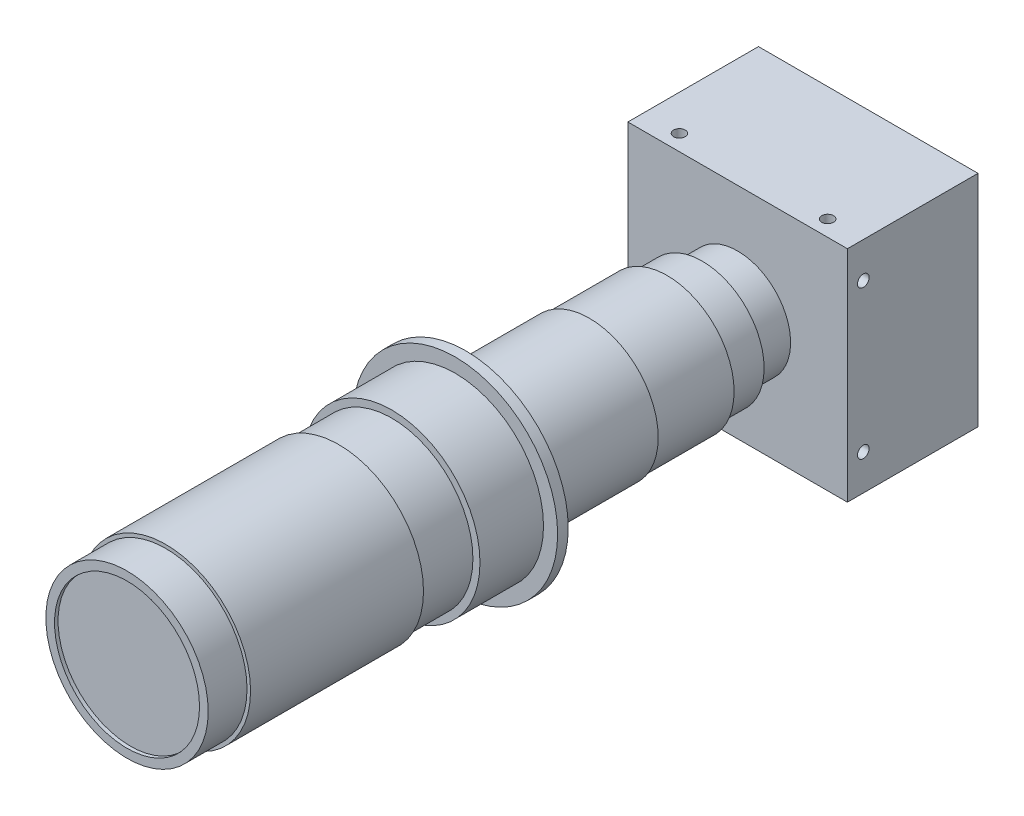
SolidWorks part; units mm, degrees
material "铝合金 (2)"
ref_plane "前基準面" through (0, 0, 0) normal (0, 0, 1) x (1, 0, 0)
ref_plane "上基準面" through (0, 0, 0) normal (0, 1, 0) x (1, 0, 0)
ref_plane "右基準面" through (0, 0, 0) normal (1, 0, 0) x (0, 0, -1)
sketch "草图1" plane through (0, 0, 0) normal (0, 0, 1) x (1, 0, 0)
  line L1 (0, 0) -> (62.2, 0)
  line L2 (0, 0) -> (0, 62.2)
  line L3 (0, 62.2) -> (62.2, 62.2)
  line L4 (62.2, 0) -> (62.2, 62.2)
  dimension "D1" = 62.2
extrude "凸台-拉伸1" add sketch "草图1" along normal blind 37
sketch "草图2" plane through (0, 0, 37) normal (0, 0, 1) x (1, 0, 0)
  line L0 (31.1, 62.2) -> (31.1, 0) construction
  line L1 (62.2, 62.2) -> (0, 62.2) construction
  line L2 (0, 0) -> (62.2, 0) construction
  circle A0 centre (31.1, 31.1) radius 15
  dimension "D1" = 30
extrude "凸台-拉伸2" add sketch "草图2" along normal blind 10
sketch "草图3" plane through (0, 0, 47) normal (0, 0, 1) x (1, 0, 0)
  circle A0 centre (31.1, 31.1) radius 17.5
  dimension "D1" = 35
extrude "凸台-拉伸3" add sketch "草图3" along normal blind 10
sketch "草图4" plane through (0, 0, 57) normal (0, 0, 1) x (1, 0, 0)
  circle A0 centre (31.1, 31.1) radius 19
  dimension "D1" = 38
extrude "凸台-拉伸4" add sketch "草图4" along normal blind 22
sketch "草图5" plane through (0, 0, 79) normal (0, 0, 1) x (1, 0, 0)
  circle A0 centre (31.1, 31.1) radius 19.5
  dimension "D1" = 39
extrude "凸台-拉伸5" add sketch "草图5" along normal blind 35
sketch "草图6" plane through (0, 0, 114) normal (0, 0, 1) x (1, 0, 0)
  circle A0 centre (31.1, 31.1) radius 29
  dimension "D1" = 58
extrude "凸台-拉伸6" add sketch "草图6" along normal blind 3
sketch "草图7" plane through (0, 0, 117) normal (0, 0, 1) x (1, 0, 0)
  circle A0 centre (31.1, 31.1) radius 25
  dimension "D1" = 50
extrude "凸台-拉伸7" add sketch "草图7" along normal blind 18
sketch "草图8" plane through (0, 0, 135) normal (0, 0, 1) x (1, 0, 0)
  circle A0 centre (31.1, 31.1) radius 23
  dimension "D1" = 46
sketch "草图9" plane through (0, 0, 0) normal (0, 0, -1) x (-1, 0, 0)
  circle A0 centre (-16.5763, 47.3033) radius 3.4696
  circle A1 centre (-16.5763, 47.3033) radius 4.9876
extrude "凸台-拉伸8" add sketch "草图9" along normal blind 7
sketch "草图10" plane through (0, 0, 0) normal (0, 0, -1) x (-1, 0, 0)
  line L1 (-24.6285, 18.2507) -> (-16.4054, 18.2507)
  line L2 (-24.6285, 18.2507) -> (-24.6285, 13.1265)
  line L3 (-24.6285, 13.1265) -> (-16.4054, 13.1265)
  line L4 (-16.4054, 18.2507) -> (-16.4054, 13.1265)
extrude "切除-拉伸2" cut sketch "草图10" against normal blind 3
hole_wizard "M4 螺纹孔1" positions "草图12" profile "草图11" tap size "M4" standard "ISO"
sketch "草图12" plane through (0, 62.2, 0) normal (0, 1, 0) x (-1, 0, 0)
  line L0 (-31.1, 37) -> (-31.1, 20.8859) construction
  line L1 (-62.2, 37) -> (0, 37) construction
  point P0 (-10.1, 32.5)
  point P1 (-52.1, 32.5)
  dimension "D1" = 42
  dimension "D2" = 4.5
sketch "草图11" plane through (10.1, 62.2, 32.5) normal (1, 0, 0) x (0, 0, 1)
  line L0 (0, 0) -> (0, 11.0914)
  line L1 (0, 11.0914) -> (1.65, 10.1)
  line L2 (1.65, 10.1) -> (1.65, 0)
  line L5 (1.65, 0) -> (0, 0)
  line L10 (0, 11.0914) -> (-1.65, 10.1) construction
  line L11 (0, -6.35) -> (0, 107.95) construction
  dimension "螺纹孔钻头直径" = 3.3
  dimension "螺纹孔钻头深度" = 10.1
  dimension "导头角度" = 118
cosmetic thread "孔螺蚊线1" parameters "D1"=8, "D2"=4
cosmetic thread "孔螺蚊线2" parameters "D1"=8, "D2"=4
hole_wizard "M4 螺纹孔2" positions "草图14" profile "草图13" tap size "M4" standard "ISO"
sketch "草图14" plane through (62.2, 0, 0) normal (1, 0, 0) x (0, 0, -1)
  line L0 (-37, 31.1) -> (-25.6315, 31.1) construction
  line L1 (-37, 0) -> (-37, 62.2) construction
  point P0 (-32.5, 10.1)
  point P1 (-32.5, 52.1)
  dimension "D1" = 4.5
  dimension "D2" = 42
sketch "草图13" plane through (62.2, 10.1, 32.5) normal (0, 1, 0) x (0, 0, -1)
  line L0 (0, 0) -> (0, 11.0914)
  line L1 (0, 11.0914) -> (1.65, 10.1)
  line L2 (1.65, 10.1) -> (1.65, 0)
  line L5 (1.65, 0) -> (0, 0)
  line L10 (0, 11.0914) -> (-1.65, 10.1) construction
  line L11 (0, -6.35) -> (0, 107.95) construction
  dimension "螺纹孔钻头直径" = 3.3
  dimension "螺纹孔钻头深度" = 10.1
  dimension "导头角度" = 118
cosmetic thread "孔螺蚊线3" parameters "D1"=8, "D2"=4
cosmetic thread "孔螺蚊线4" parameters "D1"=8, "D2"=4
hole_wizard "M4 螺纹孔3" positions "草图16" profile "草图15" tap size "M4" standard "ISO"
sketch "草图16" plane through (0, 0, 0) normal (0, -1, 0) x (1, 0, 0)
  line L0 (31.1, 37) -> (31.1, 26.6089) construction
  line L1 (0, 37) -> (62.2, 37) construction
  point P0 (10.1, 32.5)
  point P1 (52.1, 32.5)
  dimension "D1" = 42
  dimension "D2" = 4.5
sketch "草图15" plane through (10.1, 0, 32.5) normal (1, 0, 0) x (0, 0, -1)
  line L0 (0, 0) -> (0, 11.0914)
  line L1 (0, 11.0914) -> (1.65, 10.1)
  line L2 (1.65, 10.1) -> (1.65, 0)
  line L5 (1.65, 0) -> (0, 0)
  line L10 (0, 11.0914) -> (-1.65, 10.1) construction
  line L11 (0, -6.35) -> (0, 107.95) construction
  dimension "螺纹孔钻头直径" = 3.3
  dimension "螺纹孔钻头深度" = 10.1
  dimension "导头角度" = 118
cosmetic thread "孔螺蚊线5" parameters "D1"=8, "D2"=4
cosmetic thread "孔螺蚊线6" parameters "D1"=8, "D2"=4
hole_wizard "M4 螺纹孔4" positions "草图18" profile "草图17" tap size "M4" standard "ISO"
sketch "草图18" plane through (0, 0, 0) normal (-1, 0, 0) x (0, 0, 1)
  line L0 (37, 31.1) -> (21.3784, 31.1) construction
  line L1 (37, 62.2) -> (37, 0) construction
  point P0 (32.5, 52.1)
  point P1 (32.5, 10.1)
  dimension "D1" = 4.5
  dimension "D2" = 42
sketch "草图17" plane through (0, 52.1, 32.5) normal (0, 1, 0) x (0, 0, 1)
  line L0 (0, 0) -> (0, 11.0914)
  line L1 (0, 11.0914) -> (1.65, 10.1)
  line L2 (1.65, 10.1) -> (1.65, 0)
  line L5 (1.65, 0) -> (0, 0)
  line L10 (0, 11.0914) -> (-1.65, 10.1) construction
  line L11 (0, -6.35) -> (0, 107.95) construction
  dimension "螺纹孔钻头直径" = 3.3
  dimension "螺纹孔钻头深度" = 10.1
  dimension "导头角度" = 118
cosmetic thread "孔螺蚊线7" parameters "D1"=8, "D2"=4
cosmetic thread "孔螺蚊线8" parameters "D1"=8, "D2"=4
extrude "凸台-拉伸9" add sketch "草图8" along normal blind 15 separate body
sketch "草图19" plane through (0, 0, 150) normal (0, 0, 1) x (1, 0, 0)
  circle A0 centre (31.1, 31.1) radius 24
  dimension "D1" = 48
extrude "凸台-拉伸10" add sketch "草图19" along normal blind 49 separate body
sketch "草图20" plane through (0, 0, 199) normal (0, 0, 1) x (1, 0, 0)
  circle A0 centre (31.1, 31.1) radius 23
  dimension "D1" = 46
extrude "凸台-拉伸11" add sketch "草图20" along normal blind 11
sketch "草图21" plane through (0, 0, 210) normal (0, 0, 1) x (1, 0, 0)
  circle A0 centre (31.1, 31.1) radius 20.5379
extrude "切除-拉伸3" cut sketch "草图21" against normal blind 1
